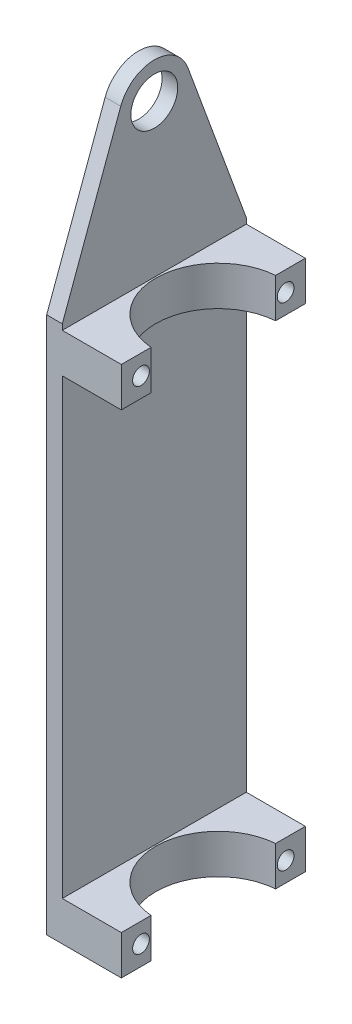
SolidWorks part; units mm, degrees
material "ABS"
ref_plane "Front Plane" through (0, 0, 0) normal (0, 0, 1) x (1, 0, 0)
ref_plane "Top Plane" through (0, 0, 0) normal (0, 1, 0) x (1, 0, 0)
ref_plane "Right Plane" through (0, 0, 0) normal (1, 0, 0) x (0, 0, -1)
sketch "Sketch1" plane through (0, 0, 0) normal (1, 0, 0) x (0, 0, -1)
  line L0 (-14.7, 0) -> (14.7, 0) construction
  line L1 (0, 0) -> (0, 35) construction
  line L2 (-14.7, 0) -> (0, 35) construction
  line L3 (0, 35) -> (14.7, 0) construction
  line L4 (14.7, 0) -> (-14.7, 0) construction
  line L8 (-14.7, 0) -> (14.7, 0) construction
  line L9 (-14.7, 0) -> (-14.7, -100) construction
  line L10 (14.7, 0) -> (14.7, -100) construction
  line L11 (-14.7, -100) -> (14.7, -100) construction
  line L16 (-18.7, -104) -> (18.7, -104)
  line L17 (-18.7, -104) -> (-18.7, 5.15)
  line L18 (18.7, -104) -> (18.7, 5.15)
  line L19 (-18.7, 5.15) -> (18.7, 5.15) construction
  line L20 (-18.7, 5.15) -> (-6.8172, 37.5038)
  line L21 (-6.8172, 37.5038) -> (6.8172, 37.5038) construction
  line L22 (6.8172, 37.5038) -> (18.7, 5.15)
  circle A0 centre (-14.7, 0) radius 3.2 construction
  circle A1 centre (0, 35) radius 4.7625
  circle A2 centre (14.7, 0) radius 3.2 construction
  circle A3 centre (-14.7, -100) radius 3.2 construction
  circle A4 centre (14.7, -100) radius 3.2 construction
  arc A5 (-6.8172, 37.5038) -> (6.8172, 37.5038) centre (0, 35) cw
  point P4 (0, 0)
  point P7 (0, -104)
  dimension "D3" = 6.4
  dimension "D4" = 9.525
  dimension "D9" = 2.5
  dimension "D2" = 4
  dimension "D1" = 29.4
  dimension "D5" = 100
  dimension "D6" = 4
  dimension "D7" = 35
  dimension "D8" = 5.15
extrude "Boss-Extrude1" add sketch "Sketch1" along normal blind 3.175
sketch "Sketch2" plane through (3.175, 0, 0) normal (1, 0, 0) x (0, 0, -1)
  line L0 (-18.7, -4) -> (18.7, -4)
  line L1 (-18.7, -4) -> (-18.7, 4)
  line L2 (18.7, -4) -> (18.7, 4)
  line L3 (-18.7, 4) -> (18.7, 4)
  line L4 (-18.7, -4) -> (18.7, 4) construction
  line L5 (18.7, -4) -> (-18.7, 4) construction
  line L6 (-18.7, -104) -> (18.7, -104)
  line L7 (-18.7, -104) -> (-18.7, -96)
  line L8 (18.7, -104) -> (18.7, -96)
  line L9 (-18.7, -96) -> (18.7, -96)
  line L10 (-18.7, -104) -> (18.7, -96) construction
  line L11 (18.7, -104) -> (-18.7, -96) construction
  line L12 (18.7, -104) -> (18.7, 5.15) construction
  line L14 (-14.7, -100) -> (14.7, -100) construction
  point P1 (0, 0)
  point P2 (0, -100)
  point P9 (0, 0)
  dimension "D1" = 8
extrude "Boss-Extrude2" add sketch "Sketch2" along normal blind 12
sketch "Sketch3" plane through (0, 0, 0) normal (0, 1, 0) x (1, 0, 0)
  line L1 (15.175, 18.7) -> (15.175, -18.7) construction
  circle A0 centre (16.175, 0) radius 12.7
  point P2 (27.244, -0.9071)
  point P4 (0, 0)
  point P6 (15.175, 0)
  dimension "D1" = 25.4
  dimension "D2" = 1
extrude "Cut-Extrude1" cut sketch "Sketch3" against normal through all both and the other way through all
hole_wizard "CBORE for M3 SHCS1" positions "Sketch4" profile "Sketch5" counterbore size "M3" standard "ANSI Metric" end condition up to next
sketch "Sketch4" plane through (0, 0, 0) normal (-1, 0, 0) x (0, 0, 1)
  point P11 (0, 0)
  point P12 (0, 0)
  point P13 (0, 0)
  point P17 (0, 0)
  point P18 (0, 0)
  point P31 (0, 0)
  point P32 (-14.7, 0)
  point P34 (14.7, 0)
  point P36 (14.7, -100)
  point P38 (-14.7, -100)
sketch "Sketch5" plane through (0, 0, -14.7) normal (0, 1, 0) x (0, 0, 1)
  line L0 (0, 0) -> (0, 15.175)
  line L1 (0, 15.175) -> (1.7, 15.175)
  line L3 (1.7, 15.175) -> (1.7, 3)
  line L4 (1.7, 3) -> (3.25, 3)
  line L5 (3.25, 3) -> (3.25, 0)
  line L7 (3.25, 0) -> (0, 0)
  line L11 (0, -6.35) -> (0, 107.95) construction
  dimension "Thru Hole Dia." = 3.4
  dimension "Thru Hole Depth" = 15.175
  dimension "C'Bore Dia." = 6.5
  dimension "C'Bore Depth" = 3
